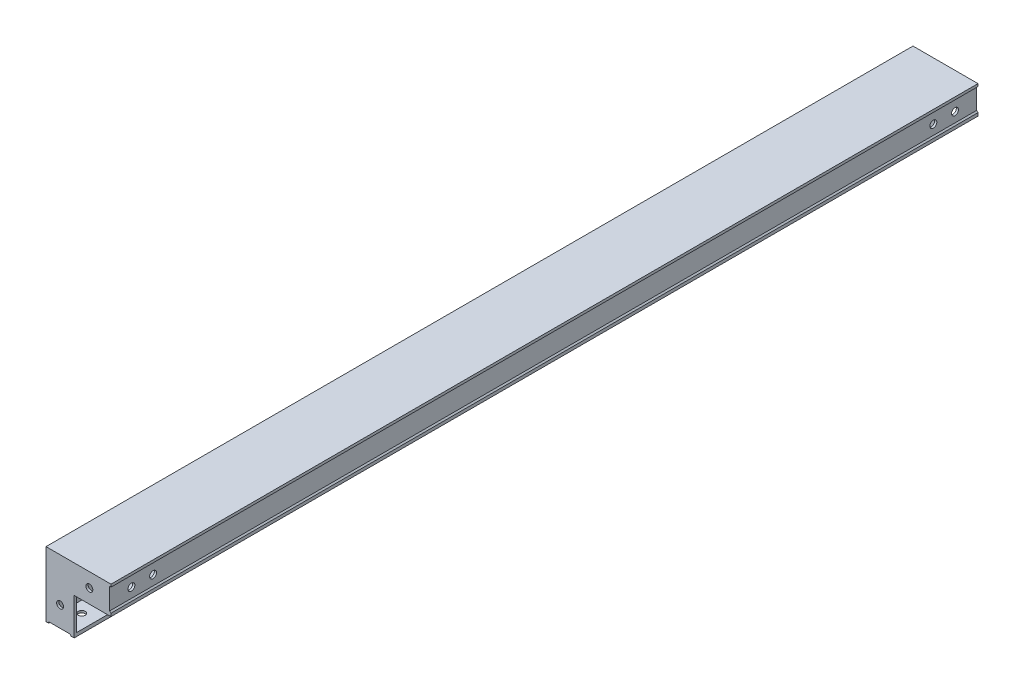
SolidWorks part; units mm, degrees
material "6061-T6 (SS)"
ref_plane "前视基准面" through (0, 0, 0) normal (0, 0, 1) x (1, 0, 0)
ref_plane "上视基准面" through (0, 0, 0) normal (0, 1, 0) x (1, 0, 0)
ref_plane "右视基准面" through (0, 0, 0) normal (1, 0, 0) x (0, 0, -1)
sketch "Model" plane through (0, 0, 0) normal (0, 0, 1) x (1, 0, 0)
  line L0 (55, -147) -> (6, -147)
  line L1 (58, -150) -> (55, -147)
  line L2 (58, -150) -> (65, -150)
  line L3 (6, -150) -> (0, -150)
  line L4 (65, -150) -> (65, -142)
  line L5 (0, -150) -> (0, 0)
  line L7 (150, 0) -> (0, 0)
  line L8 (150, 0) -> (150, -6)
  line L9 (147, -6) -> (147, -55)
  line L10 (147, -55) -> (150, -58)
  line L12 (150, -58) -> (150, -65)
  line L13 (150, -65) -> (142, -65)
  line L14 (142, -65) -> (142, -6)
  line L17 (6, -142) -> (65, -142)
  line L18 (64.6643, -150) -> (65, -149.6643) construction
  line L20 (6, -150) -> (6, -147)
  line L21 (6, -142) -> (6, -9)
  line L22 (9, -6) -> (142, -6)
  line L23 (147, -6) -> (150, -6)
  arc A0 (9, -6) -> (6, -9) centre (9, -9) ccw
  point P20 (0, 0)
  dimension "D6" = 3
  dimension "D1" = 6
  dimension "D2" = 6
  dimension "D3" = 150
  dimension "D4" = 3
  dimension "D5" = 150
  dimension "D7" = 65
  dimension "D8" = 8
  dimension "D9" = 65
  dimension "D10" = 3
  dimension "D11" = 8
  dimension "D12" = 7
  dimension "D13" = 49
  dimension "D14" = 7
  dimension "D15" = 49
extrude "凸台-拉伸1" add sketch "Model" along normal blind 2000
sketch "草图2" plane through (0, 0, 2000) normal (0, 0, 1) x (1, 0, 0)
  line L0 (65, -142) -> (65, -65)
  line L1 (6, -142) -> (65, -142)
  line L2 (6, -142) -> (6, -6)
  line L3 (6, -6) -> (142, -6)
  line L4 (142, -65) -> (142, -6)
  line L5 (142, -65) -> (65, -65)
extrude "凸台-拉伸2" add sketch "草图2" against normal blind 5
ref_plane "基准面1" through (0, 0, 1000) normal (0, 0, 1) x (1, 0, 0)
mirror "镜向1" about plane through (0, 0, 1000) normal (0, 0, 1) of "凸台-拉伸2"
hole_wizard "Ø16.0 (16) 直径孔1" positions "草图3" profile "草图4" hole size "Ø16.0" standard "GB" end condition through all
sketch "草图3" plane through (0, 0, 2000) normal (0, 0, 1) x (1, 0, 0)
  line L0 (150, 0) -> (0, 0) construction
  line L1 (150, -6) -> (150, 0) construction
  line L2 (0, -150) -> (6, -150) construction
  line L3 (0, 0) -> (0, -150) construction
  point P0 (100, -32.5)
  point P2 (32.5, -100)
  dimension "D1" = 32.5
  dimension "D2" = 50
  dimension "D3" = 50
  dimension "D4" = 32.5
sketch "草图4" plane through (100, -32.5, 2000) normal (1, 0, 0) x (0, -1, 0)
  line L0 (0, 0) -> (0, 2000)
  line L1 (0, 2000) -> (8, 2000)
  line L2 (8, 2000) -> (8, 0)
  line L5 (8, 0) -> (0, 0)
  line L11 (0, -6.35) -> (0, 107.95) construction
  dimension "通孔孔直径" = 16
  dimension "通孔孔深度" = 2000
hole_wizard "Ø16.0 (16) 直径孔2" positions "草图5" profile "草图6" hole size "Ø16.0" standard "GB"
sketch "草图5" plane through (147, 0, 0) normal (1, 0, 0) x (0, 0, -1)
  line L0 (-2000, 0) -> (0, 0) construction
  line L1 (-2000, -55) -> (-2000, -6) construction
  line L2 (-1950, -32.5) -> (-1900, -32.5) construction
  line L3 (-100, -32.5) -> (-50, -32.5) construction
  line L5 (0, -55) -> (0, -6) construction
  point P0 (-1950, -32.5)
  point P8 (-1900, -32.5)
  point P14 (-50, -32.5)
  point P16 (-100, -32.5)
  dimension "D1" = 32.5
  dimension "D2" = 50
  dimension "D3" = 50
  dimension "D4" = 32.5
  dimension "D5" = 50
  dimension "D6" = 50
sketch "草图6" plane through (147, -32.5, 1950) normal (0, 1, 0) x (0, 0, -1)
  line L0 (0, 0) -> (0, 5)
  line L1 (0, 5) -> (8, 5)
  line L2 (8, 5) -> (8, 0)
  line L5 (8, 0) -> (0, 0)
  line L11 (0, -6.35) -> (0, 107.95) construction
  dimension "通孔孔直径" = 16
  dimension "通孔孔深度" = 5
hole_wizard "Ø16.0 (16) 直径孔3" positions "草图7" profile "草图8" hole size "Ø16.0" standard "GB"
sketch "草图7" plane through (0, -147, 0) normal (0, -1, 0) x (-1, 0, 0)
  line L0 (0, -2000) -> (0, 0) construction
  line L1 (-32.5, -1950) -> (-32.5, -1868.8076)
  line L2 (-32.5, -50) -> (-32.5, -100)
  line L4 (-6, 0) -> (-55, 0) construction
  point P0 (-32.5, -1950)
  point P2 (-32.5, -1900)
  point P13 (-32.5, -50)
  point P15 (-32.5, -100)
  dimension "D1" = 32.5
  dimension "D2" = 50
  dimension "D3" = 50
  dimension "D4" = 32.5
  dimension "D5" = 50
  dimension "D6" = 50
sketch "草图8" plane through (32.5, -147, 1950) normal (1, 0, 0) x (0, 0, -1)
  line L0 (0, 0) -> (0, 5)
  line L1 (0, 5) -> (8, 5)
  line L2 (8, 5) -> (8, 0)
  line L5 (8, 0) -> (0, 0)
  line L11 (0, -6.35) -> (0, 107.95) construction
  dimension "通孔孔直径" = 16
  dimension "通孔孔深度" = 5
